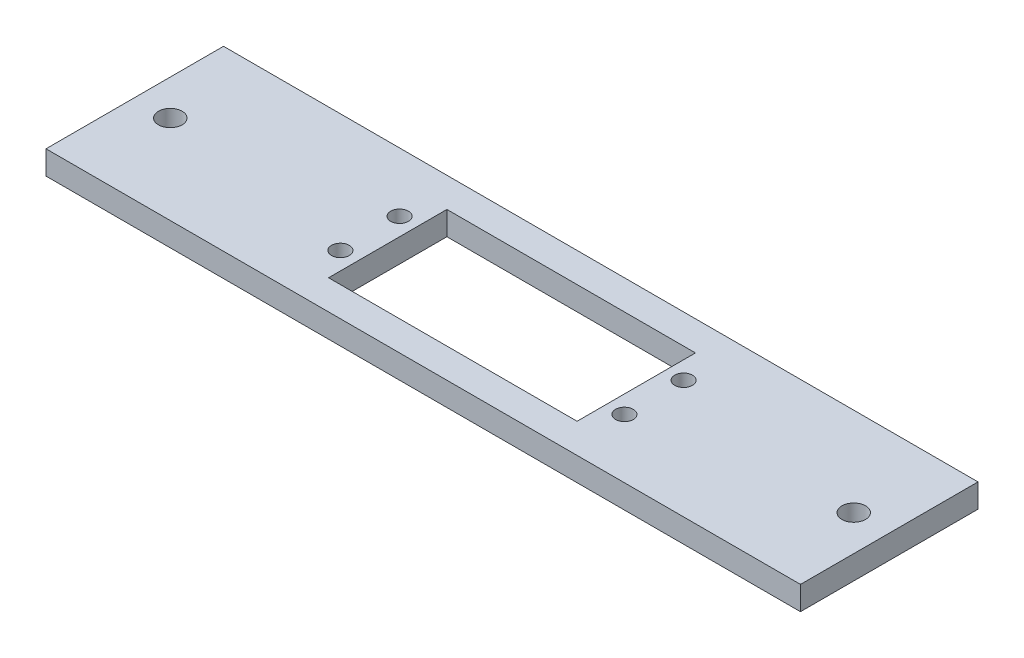
SolidWorks part; units mm, degrees
material "Balsa"
ref_plane "Front Plane" through (0, 0, 0) normal (0, 0, 1) x (1, 0, 0)
ref_plane "Top Plane" through (0, 0, 0) normal (0, 1, 0) x (1, 0, 0)
ref_plane "Right Plane" through (0, 0, 0) normal (1, 0, 0) x (0, 0, -1)
sketch "Sketch1" plane through (0, 0, 0) normal (0, 1, 0) x (1, 0, 0)
  line L0 (-21, 10) -> (-27.75, 10) construction
  line L1 (-21, -10) -> (21, -10)
  line L2 (-21, -10) -> (-21, 10)
  line L3 (-21, 10) -> (21, 10)
  line L4 (21, -10) -> (21, 10)
  line L5 (-21, -10) -> (21, 10) construction
  line L6 (-21, 10) -> (21, -10) construction
  line L7 (-27.75, 10) -> (-27.75, -10) construction
  line L8 (-27.75, -10) -> (-21, -10) construction
  line L9 (0, 10) -> (0, -10) construction
  line L10 (27.75, -10) -> (21, -10) construction
  line L11 (27.75, 10) -> (27.75, -10) construction
  line L12 (21, 10) -> (27.75, 10) construction
  line L13 (-53.9162, 0) -> (53.9162, 0) construction
  line L14 (0, 15) -> (0, -15) construction
  line L15 (-63.75, 15) -> (63.75, 15)
  line L16 (-63.75, 15) -> (-63.75, -15)
  line L17 (-63.75, -15) -> (63.75, -15)
  line L18 (63.75, 15) -> (63.75, -15)
  line L19 (-63.75, 0) -> (63.75, 0) construction
  circle A0 centre (-57.75, 0) radius 2
  circle A1 centre (57.75, 0) radius 2
  point P0 (0, 0)
  point P14 (0, 0)
  point P27 (0, 0)
  dimension "D4" = 4
  dimension "D1" = 20
  dimension "D2" = 42
  dimension "D3" = 55.5
  dimension "D5" = 30
  dimension "D6" = 30
  dimension "D7" = 6
extrude "Boss-Extrude1" add sketch "Sketch1" along normal blind 4
sketch "Sketch2" plane through (0, 4, 0) normal (0, 1, 0) x (1, 0, 0)
  line L0 (0, 15) -> (0, -15) construction
  line L1 (63.75, 15) -> (-63.75, 15) construction
  line L2 (-63.75, -15) -> (63.75, -15) construction
  line L3 (-63.75, 0) -> (63.75, 0) construction
  line L4 (-63.75, 15) -> (-63.75, -15) construction
  line L5 (63.75, -15) -> (63.75, 15) construction
  line L6 (-24, 15) -> (-24, -15) construction
  line L7 (24, 15) -> (24, -15) construction
  circle A0 centre (-24, 5) radius 1.5
  circle A1 centre (-24, -5) radius 1.5
  circle A2 centre (24, -5) radius 1.5
  circle A3 centre (24, 5) radius 1.5
  dimension "D1" = 3
  dimension "D3" = 48
  dimension "D2" = 10
extrude "Cut-Extrude1" cut sketch "Sketch2" against normal through all
